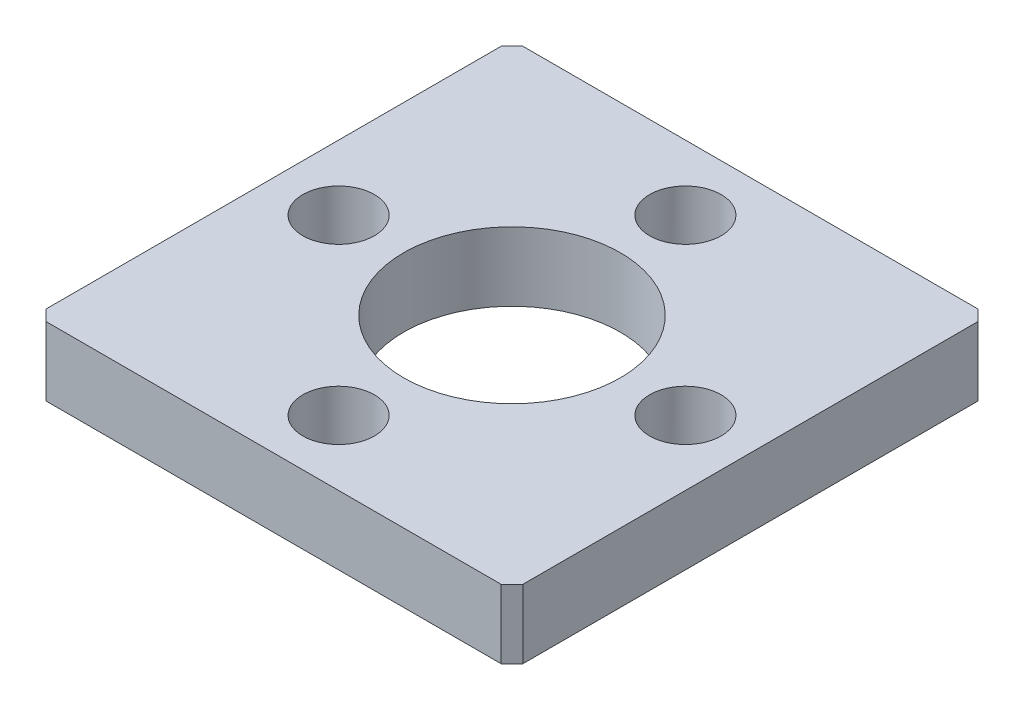
SolidWorks part; units mm, degrees
ref_plane "Front Plane" through (0, 0, 0) normal (0, 0, 1) x (1, 0, 0)
ref_plane "Top Plane" through (0, 0, 0) normal (0, 1, 0) x (1, 0, 0)
ref_plane "Right Plane" through (0, 0, 0) normal (1, 0, 0) x (0, 0, -1)
sketch "Sketch1" plane through (0, 0, 0) normal (0, 1, 0) x (1, 0, 0)
  line L1 (-11, -11) -> (11, -11)
  line L2 (-11, -11) -> (-11, 11)
  line L3 (-11, 11) -> (11, 11)
  line L4 (11, -11) -> (11, 11)
  line L5 (-11, -11) -> (11, 11) construction
  line L6 (-11, 11) -> (11, -11) construction
  point P0 (0, 0)
  dimension "D1" = 22
extrude "Boss-Extrude1" add sketch "Sketch1" along normal blind 3.175
sketch "Sketch2" plane through (0, 3.175, 0) normal (0, 1, 0) x (1, 0, 0)
  circle A0 centre (0, 0) radius 5
  dimension "D1" = 10
extrude "Cut-Extrude1" cut sketch "Sketch2" against normal through all
chamfer "Chamfer1" distance 0.5 angle 45 4 edges at (-11, 1.5875, -11) (11, 1.5875, -11) (11, 1.5875, 11) (-11, 1.5875, 11)
hole_wizard "Ø3.0mm Dowel Hole1" positions "Sketch3" profile "Sketch4" hole size "Ø3.0" standard "ANSI Metric"
sketch "Sketch3" plane through (0, 3.175, 0) normal (0, 1, 0) x (1, 0, 0)
  point P17 (0, 8)
  point P20 (8, 0)
  point P23 (0, -8)
  point P26 (-8, 0)
sketch "Sketch4" plane through (0, 3.175, -8) normal (1, 0, 0) x (0, 0, 1)
  line L0 (0, 0) -> (0, 5.9914)
  line L1 (0, 5.9914) -> (1.65, 5)
  line L2 (1.65, 5) -> (1.65, 0)
  line L5 (1.65, 0) -> (0, 0)
  line L10 (0, 5.9914) -> (-1.65, 5) construction
  line L11 (0, -6.35) -> (0, 107.95) construction
  dimension "Hole Dia." = 3.3
  dimension "Hole Depth" = 5
  dimension "Drill Angle" = 118
